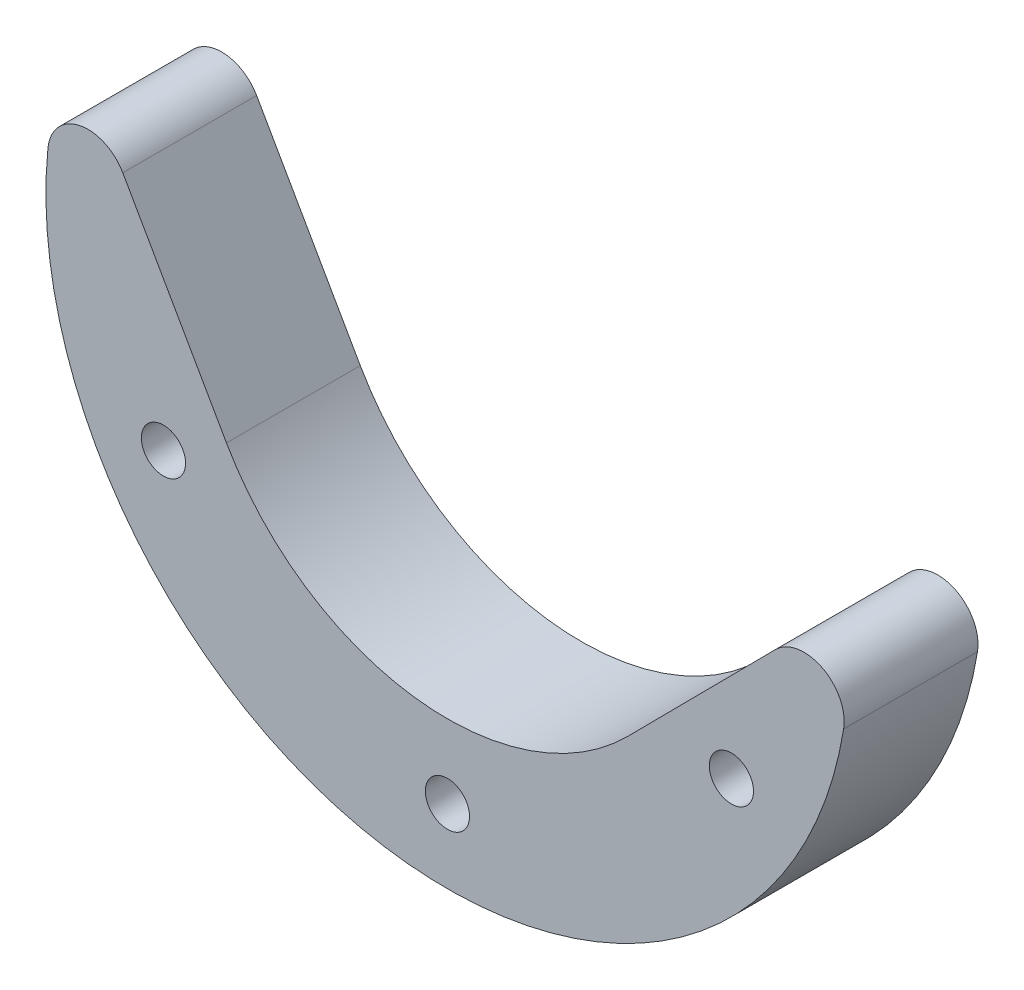
SolidWorks part; units mm, degrees
material "5052-H34"
ref_plane "正面" through (0, 0, 0) normal (0, 0, 1) x (1, 0, 0)
ref_plane "平面" through (0, 0, 0) normal (0, 1, 0) x (1, 0, 0)
ref_plane "右側面" through (0, 0, 0) normal (1, 0, 0) x (0, 0, -1)
sketch "ｽｹｯﾁ1" plane through (0, 0, 0) normal (0, 0, 1) x (1, 0, 0)
  line L0 (0, 0) -> (0, -24.5) construction
  line L1 (0, 0) -> (0, 20) construction
  line L2 (28.56, -49) -> (-28.56, -49) construction
  line L3 (28.56, -49) -> (28.56, 0) construction
  line L4 (28.56, 0) -> (-28.56, 0) construction
  line L5 (-28.56, -49) -> (-28.56, 0) construction
  line L6 (28.56, -49) -> (-28.56, 0) construction
  line L7 (28.56, 0) -> (-28.56, -49) construction
  line L8 (-25, 15) -> (-17.4226, -6.2211) construction
  line L9 (25, 25) -> (-25, 25) construction
  line L10 (25, 25) -> (25, 15) construction
  line L11 (25, 15) -> (-25, 15) construction
  line L12 (-25, 25) -> (-25, 15) construction
  line L13 (25, 25) -> (-25, 15) construction
  line L14 (25, 15) -> (-25, 25) construction
  line L15 (25, 15) -> (17.4226, -6.2211) construction
  line L16 (-16.0777, -9.152) -> (-27.2233, 10.428) construction
  line L17 (13.1407, -13.022) -> (28.9994, 2.9813) construction
  line L18 (-16.5122, -9.3993) -> (-27.9974, 10.7772)
  line L19 (13.4959, -13.3739) -> (29.8376, 3.1168)
  line L22 (0, 0) -> (-21.2176, -12.25) construction
  circle A0 centre (0, 0) radius 18.5 construction
  circle A1 centre (0, 0) radius 5.25 construction
  circle A2 centre (0, 0) radius 13.9 construction
  circle A3 centre (0, 0) radius 19
  circle A4 centre (0, -24.5) radius 1.65
  circle A5 centre (0, 0) radius 30
  circle A6 centre (-21.2176, -12.25) radius 1.65
  circle A7 centre (21.2176, -12.25) radius 1.65
  dimension "D1" = 37
  dimension "D5" = 10.5
  dimension "D6" = 27.8
  dimension "D16" = 3.3
  dimension "D17" = 60
  dimension "D18" = 24.5
  dimension "D20" = 3.3
  dimension "D11" = 22.53
  dimension "D2" = 57.12
  dimension "D3" = 49
  dimension "D4" = 0
  dimension "D7" = 10
  dimension "D8" = 50
  dimension "D9" = 20
  dimension "D10" = 22.5333
  dimension "D12" = 10
  dimension "D13" = 22.53
  dimension "D14" = 25.09
  dimension "D15" = 0.5
  dimension "D19" = 60
  dimension "D21" = 0
  dimension "D22" = 0
extrude "ﾎﾞｽ - 押し出し2" add sketch "ｽｹｯﾁ1" along normal blind 10 contours L18 A5 L19 A3 A4 A6 A7
fillet "ﾌｨﾚｯﾄ2" radius 3 2 edges at (29.8376, 3.1168, 5) (-27.9974, 10.7772, 5)
